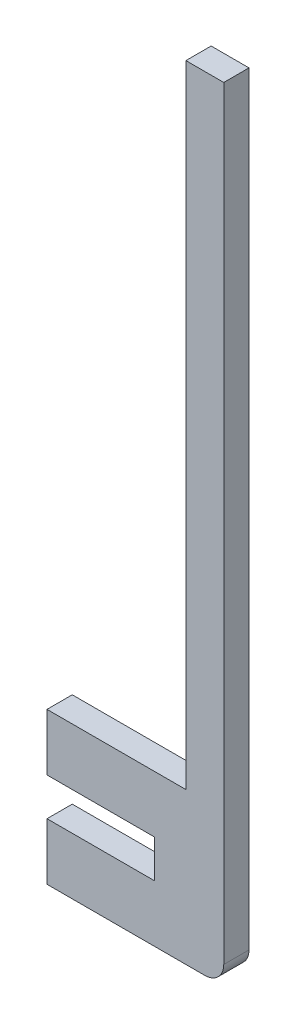
SolidWorks part; units mm, degrees
ref_plane "Front Plane" through (0, 0, 0) normal (0, 0, 1) x (1, 0, 0)
ref_plane "Top Plane" through (0, 0, 0) normal (0, 1, 0) x (1, 0, 0)
ref_plane "Right Plane" through (0, 0, 0) normal (1, 0, 0) x (0, 0, -1)
sketch "Sketch1" plane through (0, 0, 0) normal (0, 0, 1) x (1, 0, 0)
  line L0 (0, 0) -> (0, 4.5)
  line L1 (0, 4.5) -> (8.5, 4.5)
  line L2 (8.5, 4.5) -> (8.5, 7.5)
  line L3 (8.5, 7.5) -> (0, 7.5)
  line L4 (0, 7.5) -> (0, 12)
  line L5 (0, 12) -> (11, 12)
  line L6 (11, 0) -> (12.5, 0)
  line L7 (14, 1.5) -> (14, 62)
  line L8 (14, 62) -> (11, 62)
  line L9 (11, 62) -> (11, 12)
  line L11 (11, 0) -> (0, 0)
  arc A0 (12.5, 0) -> (14, 1.5) centre (12.5, 1.5) ccw
  point P17 (11, 7.5)
  dimension "D6" = 50
  dimension "D7" = 1.5
  dimension "D1" = 11
  dimension "D2" = 8.5
  dimension "D3" = 3
  dimension "D4" = 12
  dimension "D5" = 3
extrude "Boss-Extrude1" add sketch "Sketch1" along normal blind 2
